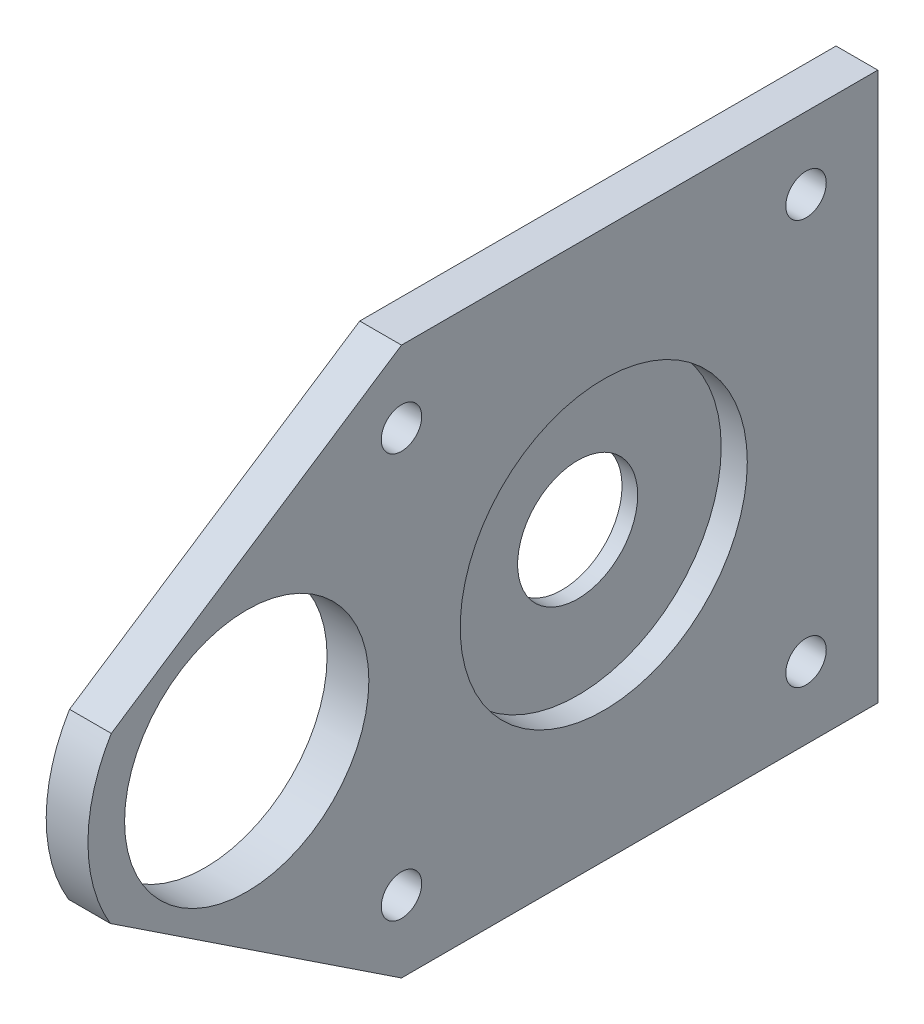
SolidWorks part; units mm, degrees
ref_plane "Front" through (0, 0, 0) normal (0, 0, 1) x (1, 0, 0)
ref_plane "Top" through (0, 0, 0) normal (0, 1, 0) x (1, 0, 0)
ref_plane "Right" through (0, 0, 0) normal (1, 0, 0) x (0, 0, -1)
sketch "Sketch1" plane through (0, 0, 0) normal (0, 0, 1) x (1, 0, 0)
  line L1 (-1.6, 21) -> (1.6, 21)
  line L2 (-1.6, 21) -> (-1.6, -21)
  line L3 (-1.6, -21) -> (1.6, -21)
  line L4 (1.6, 21) -> (1.6, -21)
extrude "Extrude1" add sketch "Sketch1" along normal blind 75
sketch "Sketch2" plane through (0, 0, 0) normal (1, 0, 0) x (0, 0, -1)
  line L0 (-36.5, 21) -> (-58.7375, 6.35)
  line L1 (-75, 21) -> (0, 21) construction
  line L2 (-36.5, 21) -> (-75, 21)
  line L3 (-75, 21) -> (-75, -21)
  line L4 (-75, -21) -> (-36.5, -21)
  line L5 (-75, -21) -> (0, -21) construction
  line L6 (-58.8122, -6.2263) -> (-36.5, -21)
  circle A0 centre (-5.5, 15.5) radius 1.55
  circle A1 centre (-5.5, -15.5) radius 1.55
  circle A2 centre (-36.5, 15.5) radius 1.55
  circle A3 centre (-36.5, -15.5) radius 1.55
  circle A4 centre (-48.36, 0) radius 9.36
  circle A6 centre (-21, 0) radius 4.6
  arc A7 (-58.7375, 6.35) -> (-58.8122, -6.2263) centre (-48.36, 0) ccw
extrude "Cut-Extrude1" cut sketch "Sketch2" against normal through all and the other way through all
sketch "Sketch3" plane through (1.6, 0, 0) normal (1, 0, 0) x (0, 0, -1)
  circle A0 centre (-21, 0) radius 11
extrude "Cut-Extrude2" cut sketch "Sketch3" against normal blind 2
